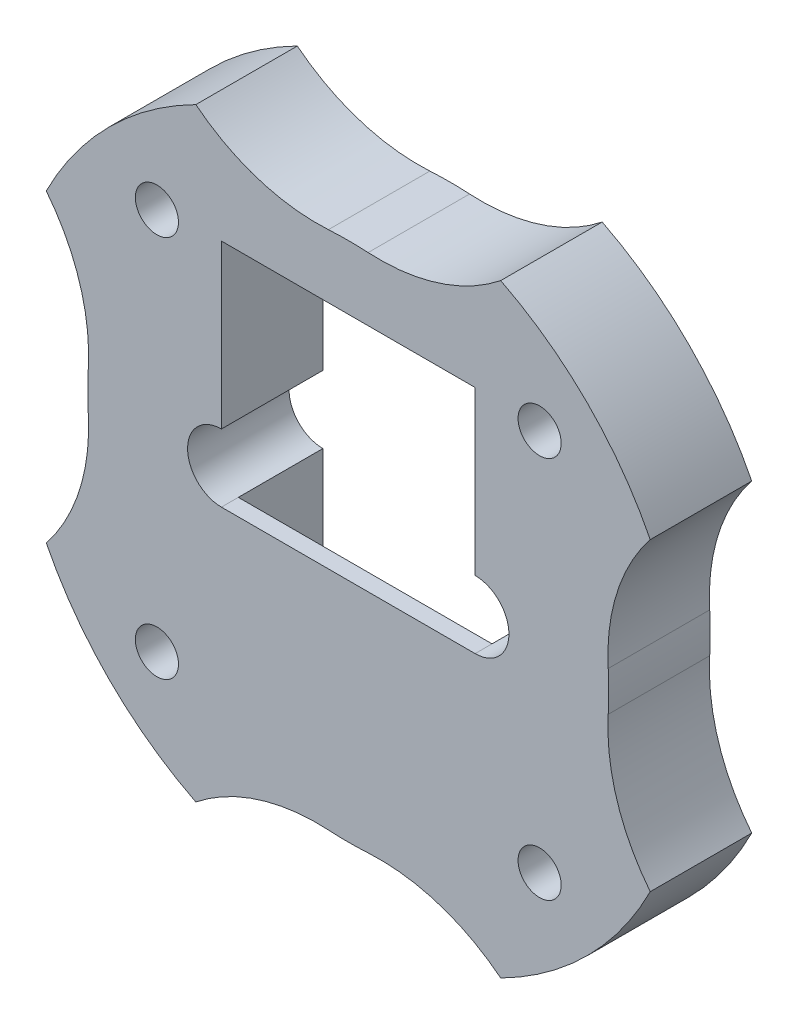
SolidWorks part; units mm, degrees
ref_plane "Front Plane" through (0, 0, 0) normal (0, 0, 1) x (1, 0, 0)
ref_plane "Top Plane" through (0, 0, 0) normal (0, 1, 0) x (1, 0, 0)
ref_plane "Right Plane" through (0, 0, 0) normal (1, 0, 0) x (0, 0, -1)
sketch "Sketch1" plane through (0, 0, 0) normal (0, 0, 1) x (1, 0, 0)
  line L0 (-15, 218.5) -> (-15, 199.25) construction
  line L1 (-15, 218.5) -> (-15, 199.25)
  line L2 (15, 245.75) -> (-15, 245.75) construction
  line L3 (15, 226.5) -> (15, 245.75) construction
  line L4 (15, 199.25) -> (15, 218.5) construction
  line L5 (-15, 199.25) -> (15, 199.25) construction
  line L6 (15, 245.75) -> (-15, 245.75)
  line L7 (15, 226.5) -> (15, 245.75)
  line L8 (15, 199.25) -> (15, 218.5)
  line L9 (-15, 199.25) -> (15, 199.25)
  line L10 (-15, 245.75) -> (-15, 226.5) construction
  line L11 (-15, 245.75) -> (-15, 226.5)
  circle A0 centre (-22.6274, 245.1274) radius 2.55 construction
  circle A1 centre (-22.6274, 245.1274) radius 2.55
  circle A2 centre (-22.6274, 199.8726) radius 2.55 construction
  circle A3 centre (-22.6274, 199.8726) radius 2.55
  circle A4 centre (22.6274, 199.8726) radius 2.55 construction
  circle A5 centre (22.6274, 199.8726) radius 2.55
  circle A6 centre (22.6274, 245.1274) radius 2.55 construction
  circle A7 centre (22.6274, 245.1274) radius 2.55
  arc A8 (-15, 226.5) -> (-15, 218.5) centre (-15, 222.5) ccw construction
  arc A9 (-15, 226.5) -> (-15, 218.5) centre (-15, 222.5) ccw
  arc A10 (15, 218.5) -> (15, 226.5) centre (15, 222.5) ccw construction
  arc A11 (15, 218.5) -> (15, 226.5) centre (15, 222.5) ccw
  arc A16 (18.0242, 186.791) -> (2.3471, 191.7594) centre (3.6966, 168.7998) ccw
  arc A17 (18.0242, 186.791) -> (35.709, 204.4758) centre (0, 222.5) ccw
  arc A18 (30.7406, 220.1529) -> (35.709, 204.4758) centre (53.7002, 218.8034) ccw
  arc A19 (30.7406, 220.1529) -> (30.7406, 224.8471) centre (-9.1905, 222.5) ccw
  arc A20 (35.709, 240.5242) -> (30.7406, 224.8471) centre (53.7002, 226.1966) ccw
  arc A21 (35.709, 240.5242) -> (18.0242, 258.209) centre (0, 222.5) ccw
  arc A22 (2.3471, 253.2406) -> (18.0242, 258.209) centre (3.6966, 276.2002) ccw
  arc A23 (2.3471, 253.2406) -> (-2.3471, 253.2406) centre (0, 213.3095) ccw
  arc A24 (-18.0242, 258.209) -> (-2.3471, 253.2406) centre (-3.6966, 276.2002) ccw
  arc A25 (-18.0242, 258.209) -> (-35.709, 240.5242) centre (0, 222.5) ccw
  arc A26 (-30.7406, 224.8471) -> (-35.709, 240.5242) centre (-53.7002, 226.1966) ccw
  arc A27 (-30.7406, 224.8471) -> (-30.7406, 220.1529) centre (9.1905, 222.5) ccw
  arc A28 (-35.709, 204.4758) -> (-30.7406, 220.1529) centre (-53.7002, 218.8034) ccw
  arc A29 (-35.709, 204.4758) -> (-18.0242, 186.791) centre (0, 222.5) ccw
  arc A30 (-2.3471, 191.7594) -> (-18.0242, 186.791) centre (-3.6966, 168.7998) ccw
  arc A31 (-2.3471, 191.7594) -> (2.3471, 191.7594) centre (0, 231.6905) ccw
  arc A32 (18.0242, 186.791) -> (2.3471, 191.7594) centre (3.6966, 168.7998) ccw
  arc A33 (18.0242, 186.791) -> (35.709, 204.4758) centre (0, 222.5) ccw
  arc A34 (30.7406, 220.1529) -> (35.709, 204.4758) centre (53.7002, 218.8034) ccw
  arc A35 (30.7406, 220.1529) -> (30.7406, 224.8471) centre (-9.1905, 222.5) ccw
  arc A36 (35.709, 240.5242) -> (30.7406, 224.8471) centre (53.7002, 226.1966) ccw
  arc A37 (35.709, 240.5242) -> (18.0242, 258.209) centre (0, 222.5) ccw
  arc A38 (2.3471, 253.2406) -> (18.0242, 258.209) centre (3.6966, 276.2002) ccw
  arc A39 (2.3471, 253.2406) -> (-2.3471, 253.2406) centre (0, 213.3095) ccw
  arc A40 (-18.0242, 258.209) -> (-2.3471, 253.2406) centre (-3.6966, 276.2002) ccw
  arc A41 (-18.0242, 258.209) -> (-35.709, 240.5242) centre (0, 222.5) ccw
  arc A42 (-30.7406, 224.8471) -> (-35.709, 240.5242) centre (-53.7002, 226.1966) ccw
  arc A43 (-30.7406, 224.8471) -> (-30.7406, 220.1529) centre (9.1905, 222.5) ccw
  arc A44 (-35.709, 204.4758) -> (-30.7406, 220.1529) centre (-53.7002, 218.8034) ccw
  arc A45 (-35.709, 204.4758) -> (-18.0242, 186.791) centre (0, 222.5) ccw
  arc A46 (-2.3471, 191.7594) -> (-18.0242, 186.791) centre (-3.6966, 168.7998) ccw
  arc A47 (-2.3471, 191.7594) -> (2.3471, 191.7594) centre (0, 231.6905) ccw
  dimension "D1" = 0
extrude "Boss-Extrude2" add sketch "Sketch1" along normal blind 10
sketch "Sketch2" plane through (0, 0, 10) normal (0, 0, 1) x (1, 0, 0)
  line L6 (-15, 245.75) -> (-15, 226.5) construction
  line L7 (15, 245.75) -> (-15, 245.75) construction
  line L8 (15, 226.5) -> (15, 245.75) construction
  line L9 (-15, 245.75) -> (-15, 226.5)
  line L10 (15, 245.75) -> (-15, 245.75)
  line L11 (15, 226.5) -> (15, 245.75)
  line L12 (-15, 218.5) -> (15, 218.5)
  arc A0 (-15, 226.5) -> (-15, 218.5) centre (-15, 222.5) ccw construction
  arc A1 (-15, 226.5) -> (-15, 218.5) centre (-15, 222.5) ccw
  arc A2 (15, 218.5) -> (15, 226.5) centre (15, 222.5) ccw construction
  arc A3 (15, 218.5) -> (15, 226.5) centre (15, 222.5) ccw
  circle A4 centre (-22.6274, 245.1274) radius 2.55 construction
  circle A5 centre (-22.6274, 245.1274) radius 2.55
  circle A6 centre (-22.6274, 199.8726) radius 2.55 construction
  circle A7 centre (-22.6274, 199.8726) radius 2.55
  circle A8 centre (22.6274, 199.8726) radius 2.55 construction
  circle A9 centre (22.6274, 199.8726) radius 2.55
  circle A10 centre (22.6274, 245.1274) radius 2.55 construction
  circle A11 centre (22.6274, 245.1274) radius 2.55
  arc A16 (18.0242, 186.791) -> (35.709, 204.4758) centre (0, 222.5) ccw
  arc A17 (30.7406, 220.1529) -> (35.709, 204.4758) centre (53.7002, 218.8034) ccw
  arc A18 (30.7406, 220.1529) -> (30.7406, 224.8471) centre (-9.1905, 222.5) ccw
  arc A19 (35.709, 240.5242) -> (30.7406, 224.8471) centre (53.7002, 226.1966) ccw
  arc A20 (35.709, 240.5242) -> (18.0242, 258.209) centre (0, 222.5) ccw
  arc A21 (2.3471, 253.2406) -> (18.0242, 258.209) centre (3.6966, 276.2002) ccw
  arc A22 (2.3471, 253.2406) -> (-2.3471, 253.2406) centre (0, 213.3095) ccw
  arc A23 (-18.0242, 258.209) -> (-2.3471, 253.2406) centre (-3.6966, 276.2002) ccw
  arc A24 (-18.0242, 258.209) -> (-35.709, 240.5242) centre (0, 222.5) ccw
  arc A25 (-30.7406, 224.8471) -> (-35.709, 240.5242) centre (-53.7002, 226.1966) ccw
  arc A26 (-30.7406, 224.8471) -> (-30.7406, 220.1529) centre (9.1905, 222.5) ccw
  arc A27 (-35.709, 204.4758) -> (-30.7406, 220.1529) centre (-53.7002, 218.8034) ccw
  arc A28 (-35.709, 204.4758) -> (-18.0242, 186.791) centre (0, 222.5) ccw
  arc A29 (-2.3471, 191.7594) -> (-18.0242, 186.791) centre (-3.6966, 168.7998) ccw
  arc A30 (-2.3471, 191.7594) -> (2.3471, 191.7594) centre (0, 231.6905) ccw
  arc A31 (18.0242, 186.791) -> (2.3471, 191.7594) centre (3.6966, 168.7998) ccw
  arc A32 (18.0242, 186.791) -> (35.709, 204.4758) centre (0, 222.5) ccw
  arc A33 (30.7406, 220.1529) -> (35.709, 204.4758) centre (53.7002, 218.8034) ccw
  arc A34 (30.7406, 220.1529) -> (30.7406, 224.8471) centre (-9.1905, 222.5) ccw
  arc A35 (35.709, 240.5242) -> (30.7406, 224.8471) centre (53.7002, 226.1966) ccw
  arc A36 (35.709, 240.5242) -> (18.0242, 258.209) centre (0, 222.5) ccw
  arc A37 (2.3471, 253.2406) -> (18.0242, 258.209) centre (3.6966, 276.2002) ccw
  arc A38 (2.3471, 253.2406) -> (-2.3471, 253.2406) centre (0, 213.3095) ccw
  arc A39 (-18.0242, 258.209) -> (-2.3471, 253.2406) centre (-3.6966, 276.2002) ccw
  arc A40 (-18.0242, 258.209) -> (-35.709, 240.5242) centre (0, 222.5) ccw
  arc A41 (-30.7406, 224.8471) -> (-35.709, 240.5242) centre (-53.7002, 226.1966) ccw
  arc A42 (-30.7406, 224.8471) -> (-30.7406, 220.1529) centre (9.1905, 222.5) ccw
  arc A43 (-35.709, 204.4758) -> (-30.7406, 220.1529) centre (-53.7002, 218.8034) ccw
  arc A44 (-35.709, 204.4758) -> (-18.0242, 186.791) centre (0, 222.5) ccw
  arc A45 (-2.3471, 191.7594) -> (-18.0242, 186.791) centre (-3.6966, 168.7998) ccw
  arc A46 (-2.3471, 191.7594) -> (2.3471, 191.7594) centre (0, 231.6905) ccw
  arc A47 (18.0242, 186.791) -> (2.3471, 191.7594) centre (3.6966, 168.7998) ccw
  dimension "D1" = 0
extrude "Boss-Extrude3" add sketch "Sketch2" along normal blind 2
